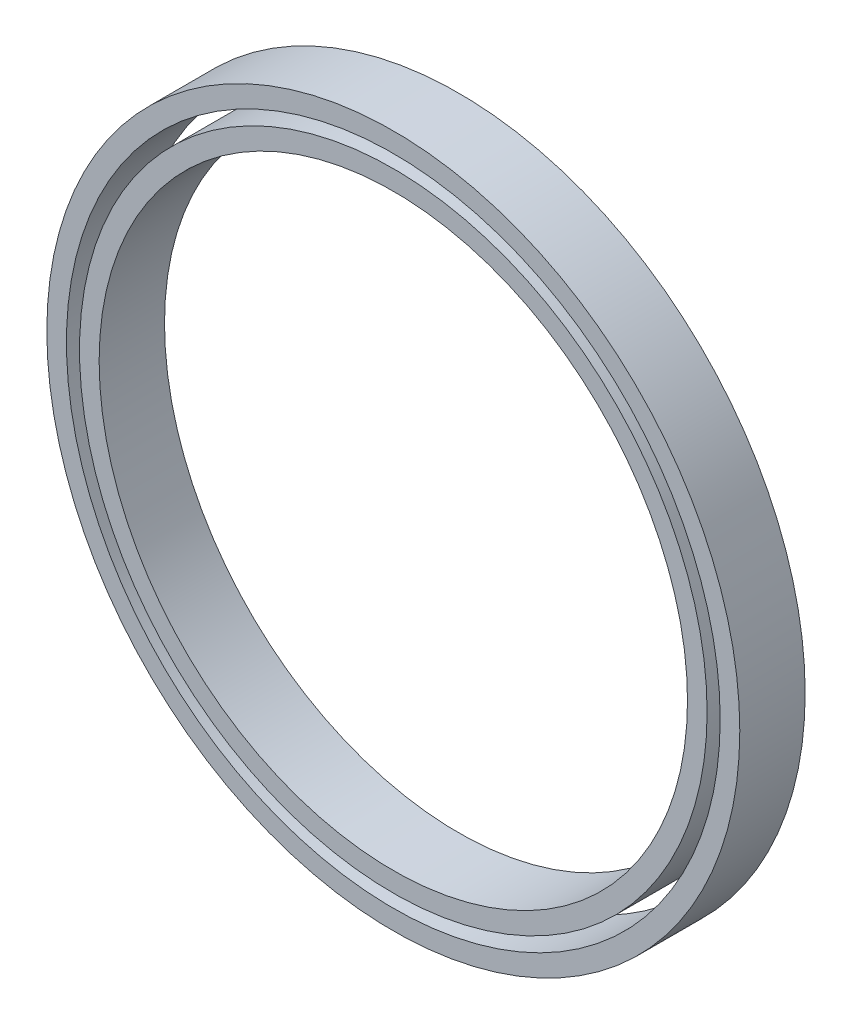
SolidWorks part; units mm, degrees
ref_plane "Front Plane" through (0, 0, 0) normal (0, 0, 1) x (1, 0, 0)
ref_plane "Top Plane" through (0, 0, 0) normal (0, 1, 0) x (1, 0, 0)
ref_plane "Right Plane" through (0, 0, 0) normal (1, 0, 0) x (0, 0, -1)
sketch "Sketch1" plane through (0, 0, 0) normal (0, 0, 1) x (1, 0, 0)
  circle A0 centre (0, 0) radius 50
  circle A1 centre (0, 0) radius 53
  circle A2 centre (0, 0) radius 45
  circle A3 centre (0, 0) radius 48
  dimension "D1" = 100
  dimension "D2" = 3
  dimension "D3" = 90
  dimension "D4" = 3
extrude "Boss-Extrude1" add sketch "Sketch1" along normal blind 10 contours A3 A2 | A1 A0
